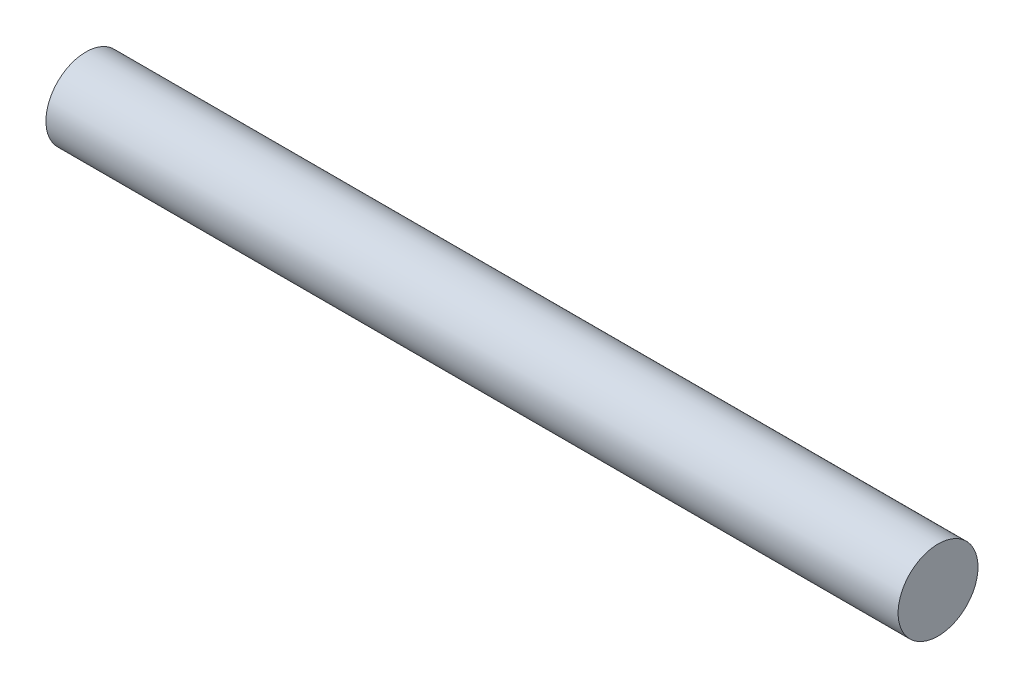
SolidWorks part; units mm, degrees
ref_plane "Front Plane" through (0, 0, 0) normal (0, 0, 1) x (1, 0, 0)
ref_plane "Top Plane" through (0, 0, 0) normal (0, 1, 0) x (1, 0, 0)
ref_plane "Right Plane" through (0, 0, 0) normal (1, 0, 0) x (0, 0, -1)
sketch "Sketch1" plane through (0, 0, 0) normal (1, 0, 0) x (0, 0, -1)
  circle A0 centre (0, 0) radius 2.3813
  dimension "D1" = 4.7625
extrude "Boss-Extrude1" add sketch "Sketch1" along normal blind 50.8
